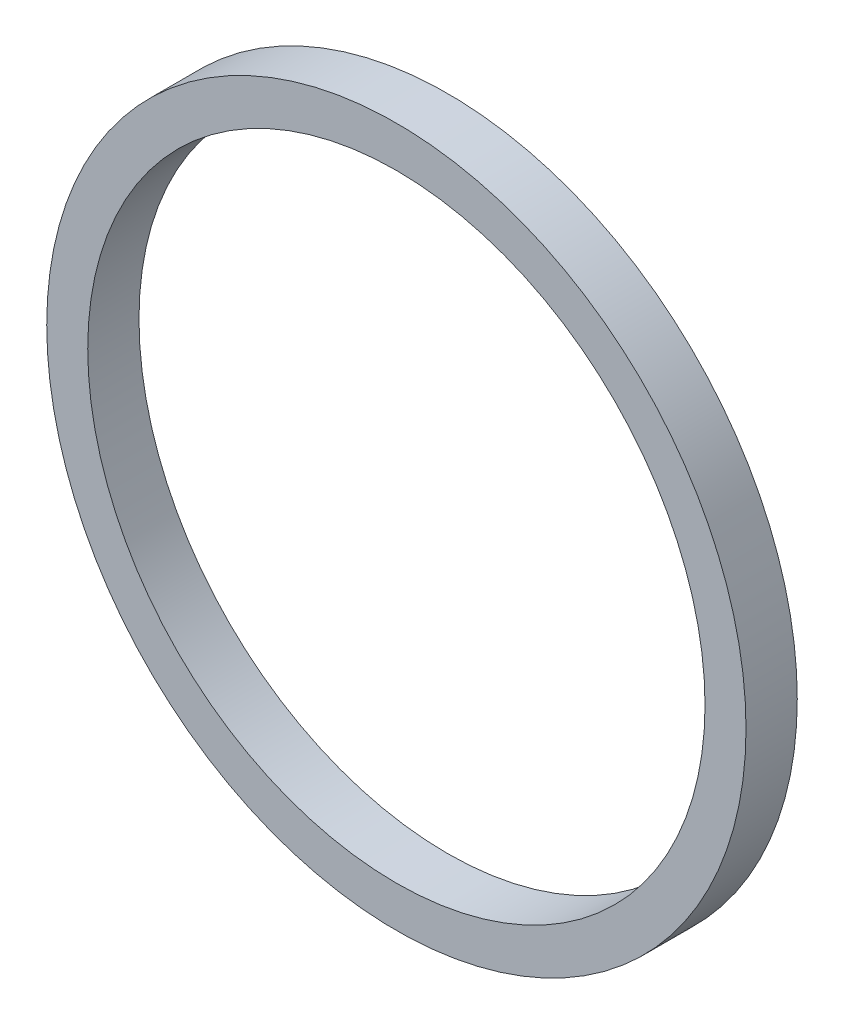
SolidWorks part; units mm, degrees
material "Acrylic (Medium-high impact)"
ref_plane "Front Plane" through (0, 0, 0) normal (0, 0, 1) x (1, 0, 0)
ref_plane "Top Plane" through (0, 0, 0) normal (0, 1, 0) x (1, 0, 0)
ref_plane "Right Plane" through (0, 0, 0) normal (1, 0, 0) x (0, 0, -1)
sketch "Sketch1" plane through (0, 0, 0) normal (0, 0, 1) x (1, 0, 0)
  circle A0 centre (0, 0) radius 17.0561
  circle A1 centre (0, 0) radius 15.0561
  circle A2 centre (0, 0) radius 17.0561 construction
  circle A3 centre (0, 0) radius 15.0561 construction
extrude "Receptacle Lightpipe" add sketch "Sketch1" against normal blind 3
other "Face Offset" face at (15.0561, 0, 0) parameters "D1"=0.5
